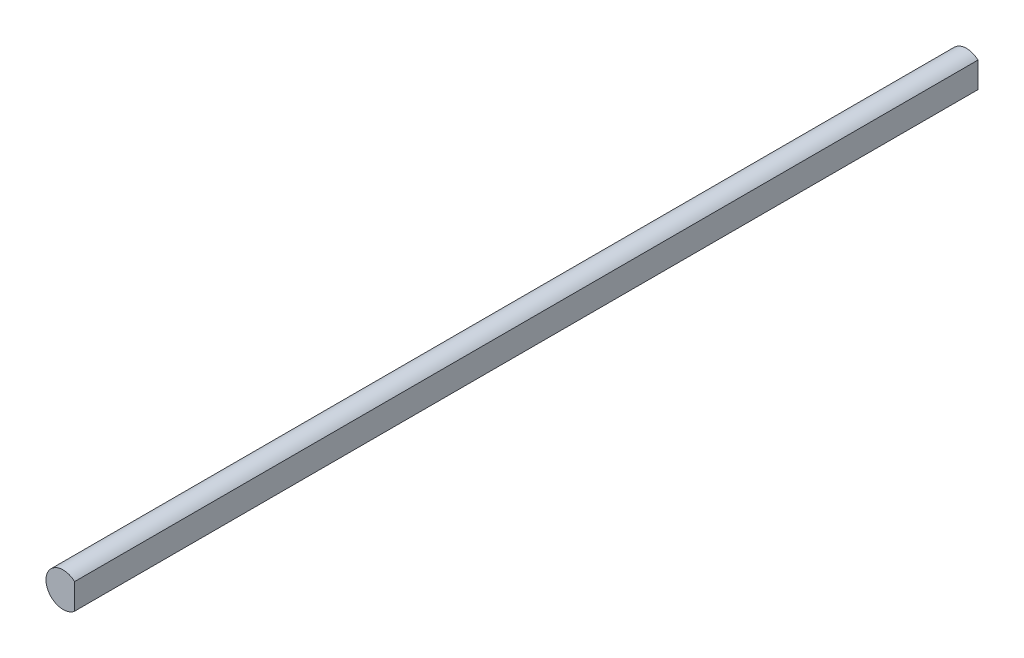
SolidWorks part; units mm, degrees
ref_plane "前视基准面" through (0, 0, 0) normal (0, 0, 1) x (1, 0, 0)
ref_plane "上视基准面" through (0, 0, 0) normal (0, 1, 0) x (1, 0, 0)
ref_plane "右视基准面" through (0, 0, 0) normal (1, 0, 0) x (0, 0, -1)
other "Configuration Table"
sketch "草图1" plane through (0, 0, 0) normal (0, 0, 1) x (1, 0, 0)
  line L0 (1, 1.118) -> (1, -1.118)
  circle A0 centre (0, 0) radius 1.5
  dimension "D1" = 3
  dimension "D2" = 1
extrude "凸台-拉伸1" add sketch "草图1" along normal blind 78.8 contours L0 A0
